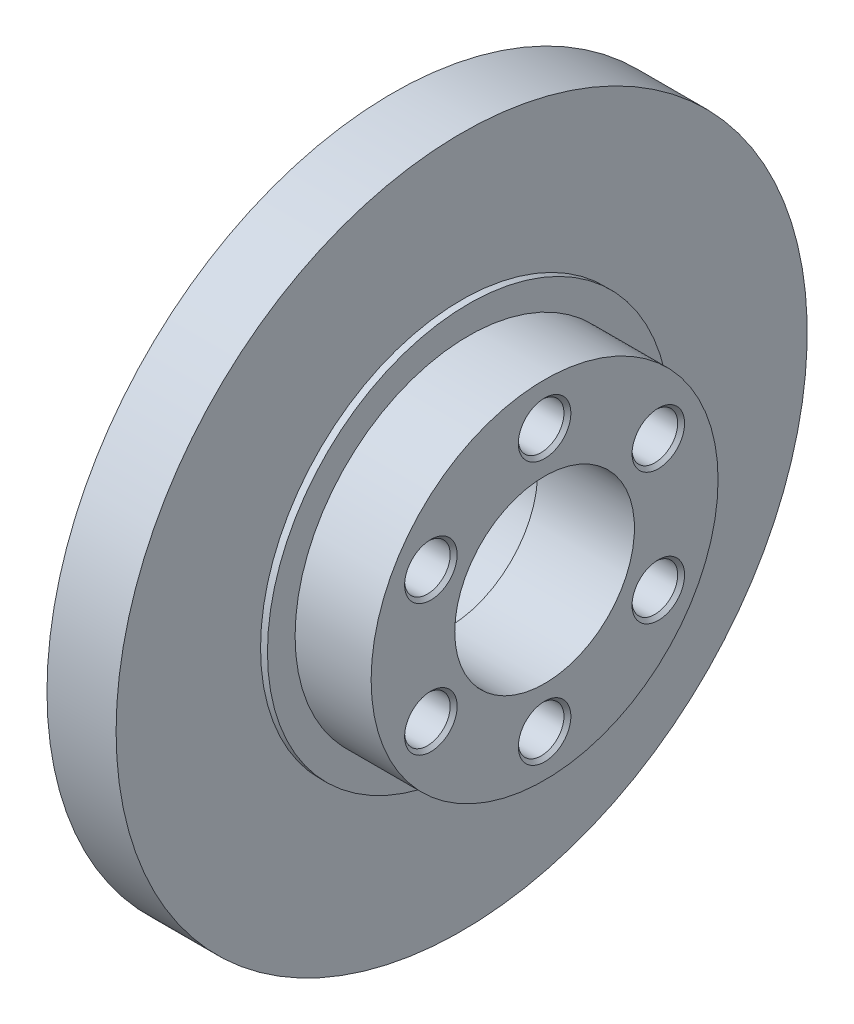
SolidWorks part; units mm, degrees
ref_plane "Front Plane" through (0, 0, 0) normal (0, 0, 1) x (1, 0, 0)
ref_plane "Top Plane" through (0, 0, 0) normal (0, 1, 0) x (1, 0, 0)
ref_plane "Right Plane" through (0, 0, 0) normal (1, 0, 0) x (0, 0, -1)
sketch "Sketch2" plane through (0, 0, 0) normal (0, 0, 1) x (1, 0, 0)
  line L0 (0, 50) -> (10, 50)
  line L1 (10, 50) -> (10, 29.1)
  line L2 (10, 29.1) -> (11, 29.1)
  line L3 (11, 29.1) -> (11, 25.1)
  line L4 (11, 25.1) -> (22, 25.1)
  line L5 (22, 25.1) -> (22, 13)
  line L6 (22, 13) -> (8, 13)
  line L9 (8, 13) -> (8, 14)
  line L10 (8, 14) -> (0, 14)
  line L11 (0, 14) -> (0, 50)
  line L12 (0, 0) -> (22, 0) construction
  dimension "D1" = 14
  dimension "D2" = 50
  dimension "D5" = 8
  dimension "14mm" = 14
  dimension "D8" = 1
  dimension "D9" = 10
  dimension "D10" = 4
  dimension "D3" = 12.1
  dimension "D4" = 13
revolve "Revolve1" add sketch "Sketch2" angle 360 about L12
sketch "Sketch3" plane through (0, 0, 0) normal (1, 0, 0) x (0, 0, -1)
  circle A0 centre (0, 0) radius 40 construction
  circle A1 centre (0, 40) radius 2.5
  circle A2 centre (28.2843, 28.2843) radius 2.5
  circle A3 centre (0, 0) radius 40 construction
  circle A4 centre (40, 0) radius 2.5
  circle A5 centre (0, 0) radius 40 construction
  circle A6 centre (28.2843, -28.2843) radius 2.5
  circle A7 centre (0, 0) radius 40 construction
  circle A8 centre (0, -40) radius 2.5
  circle A9 centre (0, 0) radius 40 construction
  circle A10 centre (-28.2843, -28.2843) radius 2.5
  circle A11 centre (0, 0) radius 40 construction
  circle A12 centre (-40, 0) radius 2.5
  circle A13 centre (0, 0) radius 40 construction
  circle A14 centre (-28.2843, 28.2843) radius 2.5
  circle A15 centre (0, 0) radius 40 construction
  point P29 (0, 0)
  dimension "D1" = 80
  dimension "D3" = 8
extrude "Cut-Extrude1" cut sketch "Sketch3" along normal blind 4
sketch "Sketch4" plane through (22, 0, 0) normal (1, 0, 0) x (0, 0, -1)
  circle A0 centre (0, 0) radius 19 construction
  circle A1 centre (0, 19) radius 3.3
  circle A2 centre (16.4545, 9.5) radius 3.3
  circle A3 centre (16.4545, -9.5) radius 3.3
  circle A4 centre (0, -19) radius 3.3
  circle A5 centre (-16.4545, -9.5) radius 3.3
  circle A6 centre (-16.4545, 9.5) radius 3.3
  point P17 (0, 0)
  dimension "D1" = 38
  dimension "D2" = 6.6
  dimension "D3" = 6
extrude "Cut-Extrude2" cut sketch "Sketch4" against normal blind 10
chamfer "Chamfer1" distance 0.5 angle 45 6 edges at (22, 9.5, 13.1545) (22, -9.5, 13.1545) (22, -19, -3.3) (22, -9.5, -19.7545) (22, 9.5, -19.7545) (22, 19, -3.3)
equation "\"R_ROLL\"= 5mm"
equation "\"D_SUN\"= 120mm"
equation "\"NUM_ROLL\"= 31"
equation "\"RHO\"= 1mm"
equation "\"D_SHAFT\"= 28mm"
equation "\"D_OUTPUT\"= 80mm"
equation "\"NUM_OUT\"= 8"
equation "\"R_OUT_ROLL\"= 5mm"
equation "\"D1@Sketch2\"=\"D_SHAFT\"/2"
equation "\"D2@Sketch2\"=\"D_OUTPUT\"/2+10"
equation "\"D1@Sketch3\"=\"D_OUTPUT\""
